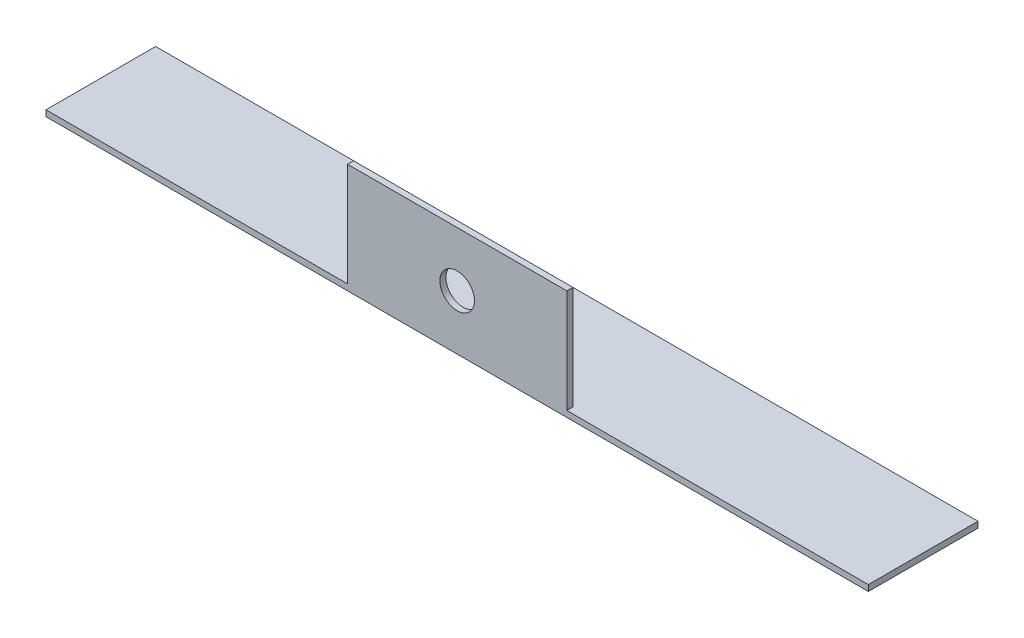
SolidWorks part; units mm, degrees
ref_plane "Front Plane" through (0, 0, 0) normal (0, 0, 1) x (1, 0, 0)
ref_plane "Top Plane" through (0, 0, 0) normal (0, 1, 0) x (1, 0, 0)
ref_plane "Right Plane" through (0, 0, 0) normal (1, 0, 0) x (0, 0, -1)
sketch "Sketch1" plane through (0, 0, 0) normal (0, 1, 0) x (1, 0, 0)
  line L1 (-190.5, 25.4) -> (190.5, 25.4)
  line L2 (-190.5, 25.4) -> (-190.5, -25.4)
  line L3 (-190.5, -25.4) -> (190.5, -25.4)
  line L4 (190.5, 25.4) -> (190.5, -25.4)
  line L5 (-190.5, 25.4) -> (190.5, -25.4) construction
  line L6 (-190.5, -25.4) -> (190.5, 25.4) construction
  point P0 (0, 0)
  dimension "D1" = 50.8
  dimension "D2" = 381
extrude "Boss-Extrude1" add sketch "Sketch1" along normal blind 2.794
sketch "Sketch2" plane through (0, 2.794, 0) normal (0, 1, 0) x (1, 0, 0)
  line L0 (190.5, -25.4) -> (190.5, 25.4) construction
  line L1 (-190.5, -25.4) -> (190.5, -25.4)
  line L2 (-190.5, -25.4) -> (-190.5, -22.606)
  line L3 (-190.5, -22.606) -> (190.5, -22.606)
  line L4 (190.5, -25.4) -> (190.5, -22.606)
  dimension "D1" = 2.794
extrude "Boss-Extrude2" add sketch "Sketch2" along normal blind 48.006
sketch "Sketch3" plane through (0, 0, 25.4) normal (0, 0, 1) x (1, 0, 0)
  line L1 (0, 50.8) -> (0, 0) construction
  line L2 (-190.5, 50.8) -> (190.5, 50.8) construction
  line L3 (-190.5, 0) -> (190.5, 0) construction
  circle A0 centre (0, 25.4) radius 8
  point P2 (0, 0)
  dimension "D1" = 16
extrude "Cut-Extrude1" cut sketch "Sketch3" against normal up to surface (2.794 mm away) up to face at (0, 26.797, 22.606)
sketch "Sketch4" plane through (0, 0, 25.4) normal (0, 0, 1) x (1, 0, 0)
  line L0 (0, 50.8) -> (0, 0) construction
  line L1 (-190.5, 50.8) -> (-50.8, 50.8)
  line L2 (-190.5, 50.8) -> (-190.5, 2.794)
  line L3 (-190.5, 2.794) -> (-50.8, 2.794)
  line L4 (-50.8, 50.8) -> (-50.8, 2.794)
  line L5 (190.5, 50.8) -> (50.8, 50.8)
  line L6 (190.5, 50.8) -> (190.5, 2.794)
  line L7 (190.5, 2.794) -> (50.8, 2.794)
  line L8 (50.8, 50.8) -> (50.8, 2.794)
  line L9 (-190.5, 50.8) -> (190.5, 50.8) construction
  point P15 (0, 25.4)
  point P18 (32.639, 67.3873)
  dimension "D1" = 48.006
  dimension "D2" = 48.006
  dimension "D3" = 50.8
  dimension "D4" = 50.8
extrude "Cut-Extrude2" cut sketch "Sketch4" against normal up to surface (2.794 mm away) up to face at (8, 25.4, 22.606)
